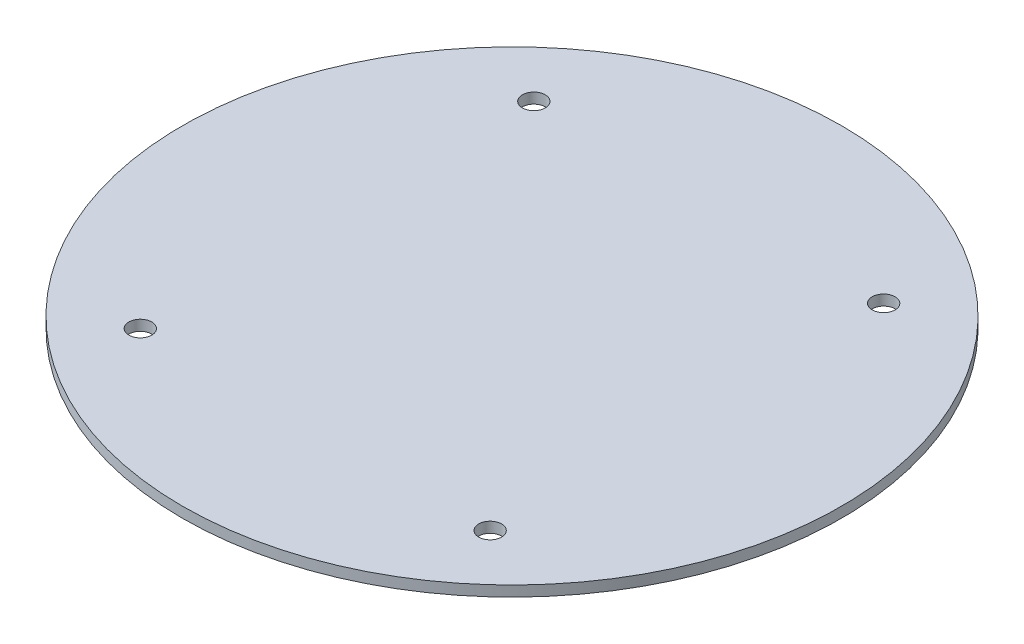
SolidWorks part; units mm, degrees
ref_plane "Front Plane" through (0, 0, 0) normal (0, 0, 1) x (1, 0, 0)
ref_plane "Top Plane" through (0, 0, 0) normal (0, 1, 0) x (1, 0, 0)
ref_plane "Right Plane" through (0, 0, 0) normal (1, 0, 0) x (0, 0, -1)
sketch "Sketch1" plane through (0, 0, 0) normal (0, 1, 0) x (1, 0, 0)
  circle A0 centre (0, 0) radius 49.78
  dimension "D1" = 99.56
extrude "Extrude1" add sketch "Sketch1" along normal blind 1.5875
sketch "Sketch2" plane through (0, 1.5875, 0) normal (0, 1, 0) x (-1, 0, 0)
  line L1 (0, 0) -> (0, -33.6111) construction
  circle A0 centre (-26.42, -29.72) radius 1.7272
  circle A1 centre (-26.42, 29.72) radius 1.7272
  dimension "D3" = 3.4544
  dimension "D6" = 3.4544
  dimension "D1" = 26.42
  dimension "D2" = 29.72
  dimension "D4" = 26.42
  dimension "D5" = 29.72
extrude "Extrude2" cut sketch "Sketch2" against normal blind 10
mirror "Mirror1" about plane through (0, 0, 0) normal (1, 0, 0) of "Extrude2"
sketch "Sketch3" plane through (0, 1.5875, 0) normal (0, 1, 0) x (-1, 0, 0)
  circle A0 centre (0, 0) radius 50.165
